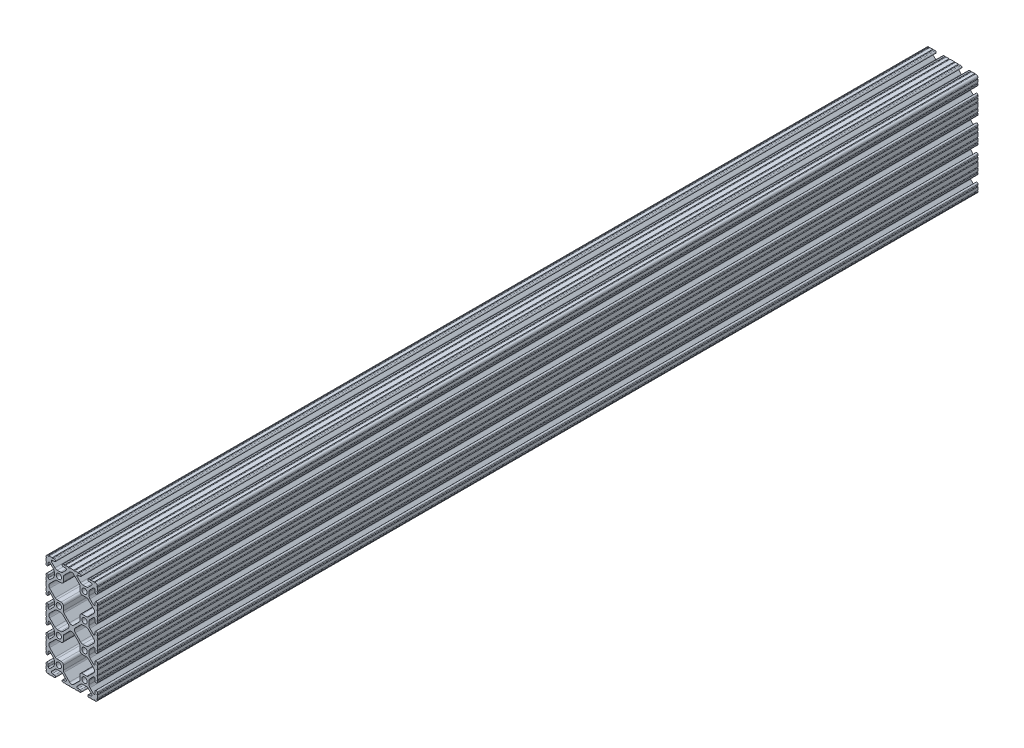
SolidWorks part; units mm, degrees
ref_plane "Front Plane" through (0, 0, 0) normal (0, 0, 1) x (1, 0, 0)
ref_plane "Top Plane" through (0, 0, 0) normal (0, 1, 0) x (1, 0, 0)
ref_plane "Right Plane" through (0, 0, 0) normal (1, 0, 0) x (0, 0, -1)
sketch "Sketch1" plane through (0, 0, 0) normal (0, 0, 1) x (1, 0, 0)
  line L0 (2.286, 55.2958) -> (-2.0184, 55.2958)
  line L1 (-3.5809, 55.943) -> (-9.0725, 61.4345)
  line L2 (-9.0725, 65.5655) -> (-3.5809, 71.057)
  line L3 (-2.0184, 71.7042) -> (2.286, 71.7042)
  line L4 (4.4958, 73.914) -> (4.4958, 78.2184)
  line L5 (5.143, 79.7809) -> (10.6345, 85.2725)
  line L6 (14.7655, 85.2725) -> (20.257, 79.7809)
  line L7 (20.9042, 78.2184) -> (20.9042, 73.914)
  line L8 (23.114, 71.7042) -> (27.4184, 71.7042)
  line L9 (28.9809, 71.057) -> (34.4725, 65.5655)
  line L10 (34.4725, 61.4345) -> (28.9809, 55.943)
  line L11 (27.4184, 55.2958) -> (23.114, 55.2958)
  line L12 (20.9042, 53.086) -> (20.9042, 48.7816)
  line L13 (20.257, 47.2191) -> (14.7655, 41.7275)
  line L14 (10.6345, 41.7275) -> (5.143, 47.2191)
  line L15 (4.4958, 48.7816) -> (4.4958, 53.086)
  line L16 (4.4958, 23.114) -> (4.4958, 27.4184)
  line L17 (5.143, 28.9809) -> (10.6345, 34.4725)
  line L18 (14.7655, 34.4725) -> (20.257, 28.9809)
  line L19 (20.9042, 27.4184) -> (20.9042, 23.114)
  line L20 (23.114, 20.9042) -> (27.4184, 20.9042)
  line L21 (28.9809, 20.257) -> (34.4725, 14.7655)
  line L22 (34.4725, 10.6345) -> (28.9809, 5.143)
  line L23 (27.4184, 4.4958) -> (23.114, 4.4958)
  line L24 (20.9042, 2.286) -> (20.9042, -2.0184)
  line L25 (20.257, -3.5809) -> (14.7655, -9.0725)
  line L26 (10.6345, -9.0725) -> (5.143, -3.5809)
  line L27 (4.4958, -2.0184) -> (4.4958, 2.286)
  line L28 (2.286, 4.4958) -> (-2.0184, 4.4958)
  line L29 (-3.5809, 5.143) -> (-9.0725, 10.6345)
  line L30 (-9.0725, 14.7655) -> (-3.5809, 20.257)
  line L31 (-2.0184, 20.9042) -> (2.286, 20.9042)
  line L32 (27.0186, 29.8958) -> (23.7824, 29.8958)
  line L33 (21.5373, 30.8258) -> (16.3286, 36.0346)
  line L34 (16.3286, 40.1654) -> (21.5373, 45.3742)
  line L35 (23.7824, 46.3042) -> (27.0186, 46.3042)
  line L36 (29.2636, 45.3743) -> (34.4725, 40.1655)
  line L37 (34.4725, 36.0345) -> (29.2636, 30.8257)
  line L38 (1.6176, 29.8958) -> (-1.6186, 29.8958)
  line L39 (-3.8636, 30.8257) -> (-9.0725, 36.0345)
  line L40 (-9.0725, 40.1655) -> (-3.8636, 45.3743)
  line L41 (-1.6186, 46.3042) -> (1.6176, 46.3042)
  line L42 (3.8627, 45.3742) -> (9.0714, 40.1654)
  line L43 (9.0714, 36.0346) -> (3.8627, 30.8258)
  line L44 (-12.7, 40.2336) -> (-12.7, 35.9664)
  line L45 (-12.7, 34.9504) -> (-12.7, 32.004)
  line L46 (-12.7, 30.988) -> (-12.7, 29.7434)
  line L47 (-10.4902, 29.7434) -> (-10.4902, 31.8743)
  line L48 (-8.7558, 32.5927) -> (-5.4258, 29.2627)
  line L49 (-4.4958, 27.0176) -> (-4.4958, 23.7824)
  line L50 (-5.4258, 21.5373) -> (-8.7558, 18.2073)
  line L51 (-10.4902, 18.9257) -> (-10.4902, 21.0566)
  line L52 (-12.7, 21.0566) -> (-12.7, 19.812)
  line L53 (-12.7, 18.796) -> (-12.7, 15.8496)
  line L54 (-12.7, 14.8336) -> (-12.7, 10.5664)
  line L55 (-12.7, 9.5504) -> (-12.7, 6.604)
  line L56 (-12.7, 5.588) -> (-12.7, 4.3434)
  line L57 (-10.4902, 4.3434) -> (-10.4902, 6.4743)
  line L58 (-8.7558, 7.1927) -> (-5.4258, 3.8627)
  line L59 (-4.4958, 1.6176) -> (-4.4958, -1.6176)
  line L60 (-5.4258, -3.8627) -> (-8.7558, -7.1927)
  line L61 (-10.4902, -6.4743) -> (-10.4902, -4.3434)
  line L62 (-12.7, -4.3434) -> (-12.7, -5.588)
  line L63 (-12.7, -6.604) -> (-12.7, -9.5504)
  line L64 (-9.5504, -12.7) -> (-6.604, -12.7)
  line L65 (-5.588, -12.7) -> (-4.3434, -12.7)
  line L66 (-4.3434, -10.4902) -> (-6.4743, -10.4902)
  line L67 (-7.1927, -8.7558) -> (-3.8627, -5.4258)
  line L68 (-1.6176, -4.4958) -> (1.6176, -4.4958)
  line L69 (3.8627, -5.4258) -> (7.1927, -8.7558)
  line L70 (6.4743, -10.4902) -> (4.3434, -10.4902)
  line L71 (4.3434, -12.7) -> (5.588, -12.7)
  line L72 (6.604, -12.7) -> (9.5504, -12.7)
  line L73 (10.5664, -12.7) -> (14.8336, -12.7)
  line L74 (15.8496, -12.7) -> (18.796, -12.7)
  line L75 (19.812, -12.7) -> (21.0566, -12.7)
  line L76 (21.0566, -10.4902) -> (18.9257, -10.4902)
  line L77 (18.2073, -8.7558) -> (21.5373, -5.4258)
  line L78 (23.7824, -4.4958) -> (27.0176, -4.4958)
  line L79 (29.2627, -5.4258) -> (32.5927, -8.7558)
  line L80 (31.8743, -10.4902) -> (29.7434, -10.4902)
  line L81 (29.7434, -12.7) -> (30.988, -12.7)
  line L82 (32.004, -12.7) -> (34.9504, -12.7)
  line L83 (38.1, -9.5504) -> (38.1, -6.604)
  line L84 (38.1, -5.588) -> (38.1, -4.3434)
  line L85 (35.8902, -4.3434) -> (35.8902, -6.4743)
  line L86 (34.1558, -7.1927) -> (30.8258, -3.8627)
  line L87 (29.8958, -1.6176) -> (29.8958, 1.6176)
  line L88 (30.8258, 3.8627) -> (34.1558, 7.1927)
  line L89 (35.8902, 6.4743) -> (35.8902, 4.3434)
  line L90 (38.1, 4.3434) -> (38.1, 5.588)
  line L91 (38.1, 6.604) -> (38.1, 9.5504)
  line L92 (38.1, 10.5664) -> (38.1, 14.8336)
  line L93 (38.1, 15.8496) -> (38.1, 18.796)
  line L94 (38.1, 19.812) -> (38.1, 21.0566)
  line L95 (35.8902, 21.0566) -> (35.8902, 18.9257)
  line L96 (34.1558, 18.2073) -> (30.8258, 21.5373)
  line L97 (29.8958, 23.7824) -> (29.8958, 27.0176)
  line L98 (30.8258, 29.2627) -> (34.1558, 32.5927)
  line L99 (35.8902, 31.8743) -> (35.8902, 29.7434)
  line L100 (38.1, 29.7434) -> (38.1, 30.988)
  line L101 (38.1, 32.004) -> (38.1, 34.9504)
  line L102 (38.1, 35.9664) -> (38.1, 40.2336)
  line L103 (38.1, 41.2496) -> (38.1, 44.196)
  line L104 (38.1, 45.212) -> (38.1, 46.4566)
  line L105 (35.8902, 46.4566) -> (35.8902, 44.3257)
  line L106 (34.1558, 43.6073) -> (30.8258, 46.9373)
  line L107 (29.8958, 49.1824) -> (29.8958, 52.4176)
  line L108 (30.8258, 54.6627) -> (34.1558, 57.9927)
  line L109 (35.8902, 57.2743) -> (35.8902, 55.1434)
  line L110 (38.1, 55.1434) -> (38.1, 56.388)
  line L111 (38.1, 57.404) -> (38.1, 60.3504)
  line L112 (38.1, 61.3664) -> (38.1, 65.6336)
  line L113 (38.1, 66.6496) -> (38.1, 69.596)
  line L114 (38.1, 70.612) -> (38.1, 71.8566)
  line L115 (35.8902, 71.8566) -> (35.8902, 69.7257)
  line L116 (34.1558, 69.0073) -> (30.8258, 72.3373)
  line L117 (29.8958, 74.5824) -> (29.8958, 77.8176)
  line L118 (30.8258, 80.0627) -> (34.1558, 83.3927)
  line L119 (35.8902, 82.6743) -> (35.8902, 80.5434)
  line L120 (38.1, 80.5434) -> (38.1, 81.788)
  line L121 (38.1, 82.804) -> (38.1, 85.7504)
  line L122 (34.9504, 88.9) -> (32.004, 88.9)
  line L123 (30.988, 88.9) -> (29.7434, 88.9)
  line L124 (29.7434, 86.6902) -> (31.8743, 86.6902)
  line L125 (32.5927, 84.9558) -> (29.2627, 81.6258)
  line L126 (27.0176, 80.6958) -> (23.7824, 80.6958)
  line L127 (21.5373, 81.6258) -> (18.2073, 84.9558)
  line L128 (18.9257, 86.6902) -> (21.0566, 86.6902)
  line L129 (21.0566, 88.9) -> (19.812, 88.9)
  line L130 (18.796, 88.9) -> (15.8496, 88.9)
  line L131 (14.8336, 88.9) -> (10.5664, 88.9)
  line L132 (9.5504, 88.9) -> (6.604, 88.9)
  line L133 (5.588, 88.9) -> (4.3434, 88.9)
  line L134 (4.3434, 86.6902) -> (6.4743, 86.6902)
  line L135 (7.1927, 84.9558) -> (3.8627, 81.6258)
  line L136 (1.6176, 80.6958) -> (-1.6176, 80.6958)
  line L137 (-3.8627, 81.6258) -> (-7.1927, 84.9558)
  line L138 (-6.4743, 86.6902) -> (-4.3434, 86.6902)
  line L139 (-4.3434, 88.9) -> (-5.588, 88.9)
  line L140 (-6.604, 88.9) -> (-9.5504, 88.9)
  line L141 (-12.7, 85.7504) -> (-12.7, 82.804)
  line L142 (-12.7, 81.788) -> (-12.7, 80.5434)
  line L143 (-10.4902, 80.5434) -> (-10.4902, 82.6743)
  line L144 (-8.7558, 83.3927) -> (-5.4258, 80.0627)
  line L145 (-4.4958, 77.8176) -> (-4.4958, 74.5824)
  line L146 (-5.4258, 72.3373) -> (-8.7558, 69.0073)
  line L147 (-10.4902, 69.7257) -> (-10.4902, 71.8566)
  line L148 (-12.7, 71.8566) -> (-12.7, 70.612)
  line L149 (-12.7, 69.596) -> (-12.7, 66.6496)
  line L150 (-12.7, 65.6336) -> (-12.7, 61.3664)
  line L151 (-12.7, 60.3504) -> (-12.7, 57.404)
  line L152 (-12.7, 56.388) -> (-12.7, 55.1434)
  line L153 (-10.4902, 55.1434) -> (-10.4902, 57.2743)
  line L154 (-8.7558, 57.9927) -> (-5.4258, 54.6627)
  line L155 (-4.4958, 52.4176) -> (-4.4958, 49.1824)
  line L156 (-5.4258, 46.9373) -> (-8.7558, 43.6073)
  line L157 (-10.4902, 44.3257) -> (-10.4902, 46.4566)
  line L158 (-12.7, 46.4566) -> (-12.7, 45.212)
  line L159 (-12.7, 44.196) -> (-12.7, 41.2496)
  arc A0 (4.4958, 53.086) -> (2.286, 55.2958) centre (2.286, 53.086) ccw
  arc A1 (-3.5809, 55.943) -> (-2.0184, 55.2958) centre (-2.0184, 57.5056) ccw
  arc A2 (-9.0725, 65.5655) -> (-9.0725, 61.4345) centre (-7.0071, 63.5) ccw
  arc A3 (-2.0184, 71.7042) -> (-3.5809, 71.057) centre (-2.0184, 69.4944) ccw
  arc A4 (2.286, 71.7042) -> (4.4958, 73.914) centre (2.286, 73.914) ccw
  arc A5 (5.143, 79.7809) -> (4.4958, 78.2184) centre (6.7056, 78.2184) ccw
  arc A6 (14.7655, 85.2725) -> (10.6345, 85.2725) centre (12.7, 83.2071) ccw
  arc A7 (20.9042, 78.2184) -> (20.257, 79.7809) centre (18.6944, 78.2184) ccw
  arc A8 (20.9042, 73.914) -> (23.114, 71.7042) centre (23.114, 73.914) ccw
  arc A9 (28.9809, 71.057) -> (27.4184, 71.7042) centre (27.4184, 69.4944) ccw
  arc A10 (34.4725, 61.4345) -> (34.4725, 65.5655) centre (32.4071, 63.5) ccw
  arc A11 (27.4184, 55.2958) -> (28.9809, 55.943) centre (27.4184, 57.5056) ccw
  arc A12 (23.114, 55.2958) -> (20.9042, 53.086) centre (23.114, 53.086) ccw
  arc A13 (20.257, 47.2191) -> (20.9042, 48.7816) centre (18.6944, 48.7816) ccw
  arc A14 (10.6345, 41.7275) -> (14.7655, 41.7275) centre (12.7, 43.7929) ccw
  arc A15 (4.4958, 48.7816) -> (5.143, 47.2191) centre (6.7056, 48.7816) ccw
  arc A16 (2.286, 20.9042) -> (4.4958, 23.114) centre (2.286, 23.114) ccw
  arc A17 (5.143, 28.9809) -> (4.4958, 27.4184) centre (6.7056, 27.4184) ccw
  arc A18 (14.7655, 34.4725) -> (10.6345, 34.4725) centre (12.7, 32.4071) ccw
  arc A19 (20.9042, 27.4184) -> (20.257, 28.9809) centre (18.6944, 27.4184) ccw
  arc A20 (20.9042, 23.114) -> (23.114, 20.9042) centre (23.114, 23.114) ccw
  arc A21 (28.9809, 20.257) -> (27.4184, 20.9042) centre (27.4184, 18.6944) ccw
  arc A22 (34.4725, 10.6345) -> (34.4725, 14.7655) centre (32.4071, 12.7) ccw
  arc A23 (27.4184, 4.4958) -> (28.9809, 5.143) centre (27.4184, 6.7056) ccw
  arc A24 (23.114, 4.4958) -> (20.9042, 2.286) centre (23.114, 2.286) ccw
  arc A25 (20.257, -3.5809) -> (20.9042, -2.0184) centre (18.6944, -2.0184) ccw
  arc A26 (10.6345, -9.0725) -> (14.7655, -9.0725) centre (12.7, -7.0071) ccw
  arc A27 (4.4958, -2.0184) -> (5.143, -3.5809) centre (6.7056, -2.0184) ccw
  arc A28 (4.4958, 2.286) -> (2.286, 4.4958) centre (2.286, 2.286) ccw
  arc A29 (-3.5809, 5.143) -> (-2.0184, 4.4958) centre (-2.0184, 6.7056) ccw
  arc A30 (-9.0725, 14.7655) -> (-9.0725, 10.6345) centre (-7.0071, 12.7) ccw
  arc A31 (-2.0184, 20.9042) -> (-3.5809, 20.257) centre (-2.0184, 18.6944) ccw
  arc A32 (27.0186, 29.8958) -> (29.2636, 30.8257) centre (27.0186, 33.0708) ccw
  arc A33 (21.5373, 30.8258) -> (23.7824, 29.8958) centre (23.7824, 33.0708) ccw
  arc A34 (16.3286, 40.1654) -> (16.3286, 36.0346) centre (18.3941, 38.1) ccw
  arc A35 (23.7824, 46.3042) -> (21.5373, 45.3742) centre (23.7824, 43.1292) ccw
  arc A36 (29.2636, 45.3743) -> (27.0186, 46.3042) centre (27.0186, 43.1292) ccw
  arc A37 (34.4725, 36.0345) -> (34.4725, 40.1655) centre (32.4071, 38.1) ccw
  arc A38 (1.6176, 29.8958) -> (3.8627, 30.8258) centre (1.6176, 33.0708) ccw
  arc A39 (-3.8636, 30.8257) -> (-1.6186, 29.8958) centre (-1.6186, 33.0708) ccw
  arc A40 (-9.0725, 40.1655) -> (-9.0725, 36.0345) centre (-7.0071, 38.1) ccw
  arc A41 (-1.6186, 46.3042) -> (-3.8636, 45.3743) centre (-1.6186, 43.1292) ccw
  arc A42 (3.8627, 45.3742) -> (1.6176, 46.3042) centre (1.6176, 43.1292) ccw
  arc A43 (9.0714, 36.0346) -> (9.0714, 40.1654) centre (7.0059, 38.1) ccw
  circle A44 centre (25.4, 76.2) radius 2.6035
  circle A45 centre (0, 76.2) radius 2.6035
  circle A46 centre (25.4, 50.8) radius 2.6035
  circle A47 centre (0, 50.8) radius 2.6035
  circle A48 centre (25.4, 0) radius 2.6035
  circle A49 centre (0, 0) radius 2.6035
  circle A50 centre (25.4, 25.4) radius 2.6035
  circle A51 centre (0, 25.4) radius 2.6035
  arc A52 (-12.7, 34.9504) -> (-12.7, 35.9664) centre (-12.7, 35.4584) ccw
  arc A53 (-12.7, 30.988) -> (-12.7, 32.004) centre (-12.7, 31.496) ccw
  arc A54 (-12.7, 29.7434) -> (-10.4902, 29.7434) centre (-11.5951, 29.7434) ccw
  arc A55 (-8.7558, 32.5927) -> (-10.4902, 31.8743) centre (-9.4742, 31.8743) ccw
  arc A56 (-4.4958, 27.0176) -> (-5.4258, 29.2627) centre (-7.6708, 27.0176) ccw
  arc A57 (-5.4258, 21.5373) -> (-4.4958, 23.7824) centre (-7.6708, 23.7824) ccw
  arc A58 (-10.4902, 18.9257) -> (-8.7558, 18.2073) centre (-9.4742, 18.9257) ccw
  arc A59 (-10.4902, 21.0566) -> (-12.7, 21.0566) centre (-11.5951, 21.0566) ccw
  arc A60 (-12.7, 18.796) -> (-12.7, 19.812) centre (-12.7, 19.304) ccw
  arc A61 (-12.7, 14.8336) -> (-12.7, 15.8496) centre (-12.7, 15.3416) ccw
  arc A62 (-12.7, 9.5504) -> (-12.7, 10.5664) centre (-12.7, 10.0584) ccw
  arc A63 (-12.7, 5.588) -> (-12.7, 6.604) centre (-12.7, 6.096) ccw
  arc A64 (-12.7, 4.3434) -> (-10.4902, 4.3434) centre (-11.5951, 4.3434) ccw
  arc A65 (-8.7558, 7.1927) -> (-10.4902, 6.4743) centre (-9.4742, 6.4743) ccw
  arc A66 (-4.4958, 1.6176) -> (-5.4258, 3.8627) centre (-7.6708, 1.6176) ccw
  arc A67 (-5.4258, -3.8627) -> (-4.4958, -1.6176) centre (-7.6708, -1.6176) ccw
  arc A68 (-10.4902, -6.4743) -> (-8.7558, -7.1927) centre (-9.4742, -6.4743) ccw
  arc A69 (-10.4902, -4.3434) -> (-12.7, -4.3434) centre (-11.5951, -4.3434) ccw
  arc A70 (-12.7, -6.604) -> (-12.7, -5.588) centre (-12.7, -6.096) ccw
  arc A71 (-12.6998, -10.5664) -> (-12.7, -9.5504) centre (-12.7, -10.0584) ccw
  arc A72 (-12.6998, -10.5664) -> (-10.5664, -12.6998) centre (-10.5918, -10.5918) ccw
  arc A73 (-9.5504, -12.7) -> (-10.5664, -12.6998) centre (-10.0584, -12.7) ccw
  arc A74 (-5.588, -12.7) -> (-6.604, -12.7) centre (-6.096, -12.7) ccw
  arc A75 (-4.3434, -12.7) -> (-4.3434, -10.4902) centre (-4.3434, -11.5951) ccw
  arc A76 (-7.1927, -8.7558) -> (-6.4743, -10.4902) centre (-6.4743, -9.4742) ccw
  arc A77 (-1.6176, -4.4958) -> (-3.8627, -5.4258) centre (-1.6176, -7.6708) ccw
  arc A78 (3.8627, -5.4258) -> (1.6176, -4.4958) centre (1.6176, -7.6708) ccw
  arc A79 (6.4743, -10.4902) -> (7.1927, -8.7558) centre (6.4743, -9.4742) ccw
  arc A80 (4.3434, -10.4902) -> (4.3434, -12.7) centre (4.3434, -11.5951) ccw
  arc A81 (6.604, -12.7) -> (5.588, -12.7) centre (6.096, -12.7) ccw
  arc A82 (10.5664, -12.7) -> (9.5504, -12.7) centre (10.0584, -12.7) ccw
  arc A83 (15.8496, -12.7) -> (14.8336, -12.7) centre (15.3416, -12.7) ccw
  arc A84 (19.812, -12.7) -> (18.796, -12.7) centre (19.304, -12.7) ccw
  arc A85 (21.0566, -12.7) -> (21.0566, -10.4902) centre (21.0566, -11.5951) ccw
  arc A86 (18.2073, -8.7558) -> (18.9257, -10.4902) centre (18.9257, -9.4742) ccw
  arc A87 (23.7824, -4.4958) -> (21.5373, -5.4258) centre (23.7824, -7.6708) ccw
  arc A88 (29.2627, -5.4258) -> (27.0176, -4.4958) centre (27.0176, -7.6708) ccw
  arc A89 (31.8743, -10.4902) -> (32.5927, -8.7558) centre (31.8743, -9.4742) ccw
  arc A90 (29.7434, -10.4902) -> (29.7434, -12.7) centre (29.7434, -11.5951) ccw
  arc A91 (32.004, -12.7) -> (30.988, -12.7) centre (31.496, -12.7) ccw
  arc A92 (35.9664, -12.6998) -> (34.9504, -12.7) centre (35.4584, -12.7) ccw
  arc A93 (35.9664, -12.6998) -> (38.0998, -10.5664) centre (35.9918, -10.5918) ccw
  arc A94 (38.1, -9.5504) -> (38.0998, -10.5664) centre (38.1, -10.0584) ccw
  arc A95 (38.1, -5.588) -> (38.1, -6.604) centre (38.1, -6.096) ccw
  arc A96 (38.1, -4.3434) -> (35.8902, -4.3434) centre (36.9951, -4.3434) ccw
  arc A97 (34.1558, -7.1927) -> (35.8902, -6.4743) centre (34.8742, -6.4743) ccw
  arc A98 (29.8958, -1.6176) -> (30.8258, -3.8627) centre (33.0708, -1.6176) ccw
  arc A99 (30.8258, 3.8627) -> (29.8958, 1.6176) centre (33.0708, 1.6176) ccw
  arc A100 (35.8902, 6.4743) -> (34.1558, 7.1927) centre (34.8742, 6.4743) ccw
  arc A101 (35.8902, 4.3434) -> (38.1, 4.3434) centre (36.9951, 4.3434) ccw
  arc A102 (38.1, 6.604) -> (38.1, 5.588) centre (38.1, 6.096) ccw
  arc A103 (38.1, 10.5664) -> (38.1, 9.5504) centre (38.1, 10.0584) ccw
  arc A104 (38.1, 15.8496) -> (38.1, 14.8336) centre (38.1, 15.3416) ccw
  arc A105 (38.1, 19.812) -> (38.1, 18.796) centre (38.1, 19.304) ccw
  arc A106 (38.1, 21.0566) -> (35.8902, 21.0566) centre (36.9951, 21.0566) ccw
  arc A107 (34.1558, 18.2073) -> (35.8902, 18.9257) centre (34.8742, 18.9257) ccw
  arc A108 (29.8958, 23.7824) -> (30.8258, 21.5373) centre (33.0708, 23.7824) ccw
  arc A109 (30.8258, 29.2627) -> (29.8958, 27.0176) centre (33.0708, 27.0176) ccw
  arc A110 (35.8902, 31.8743) -> (34.1558, 32.5927) centre (34.8742, 31.8743) ccw
  arc A111 (35.8902, 29.7434) -> (38.1, 29.7434) centre (36.9951, 29.7434) ccw
  arc A112 (38.1, 32.004) -> (38.1, 30.988) centre (38.1, 31.496) ccw
  arc A113 (38.1, 35.9664) -> (38.1, 34.9504) centre (38.1, 35.4584) ccw
  arc A114 (38.1, 41.2496) -> (38.1, 40.2336) centre (38.1, 40.7416) ccw
  arc A115 (38.1, 45.212) -> (38.1, 44.196) centre (38.1, 44.704) ccw
  arc A116 (38.1, 46.4566) -> (35.8902, 46.4566) centre (36.9951, 46.4566) ccw
  arc A117 (34.1558, 43.6073) -> (35.8902, 44.3257) centre (34.8742, 44.3257) ccw
  arc A118 (29.8958, 49.1824) -> (30.8258, 46.9373) centre (33.0708, 49.1824) ccw
  arc A119 (30.8258, 54.6627) -> (29.8958, 52.4176) centre (33.0708, 52.4176) ccw
  arc A120 (35.8902, 57.2743) -> (34.1558, 57.9927) centre (34.8742, 57.2743) ccw
  arc A121 (35.8902, 55.1434) -> (38.1, 55.1434) centre (36.9951, 55.1434) ccw
  arc A122 (38.1, 57.404) -> (38.1, 56.388) centre (38.1, 56.896) ccw
  arc A123 (38.1, 61.3664) -> (38.1, 60.3504) centre (38.1, 60.8584) ccw
  arc A124 (38.1, 66.6496) -> (38.1, 65.6336) centre (38.1, 66.1416) ccw
  arc A125 (38.1, 70.612) -> (38.1, 69.596) centre (38.1, 70.104) ccw
  arc A126 (38.1, 71.8566) -> (35.8902, 71.8566) centre (36.9951, 71.8566) ccw
  arc A127 (34.1558, 69.0073) -> (35.8902, 69.7257) centre (34.8742, 69.7257) ccw
  arc A128 (29.8958, 74.5824) -> (30.8258, 72.3373) centre (33.0708, 74.5824) ccw
  arc A129 (30.8258, 80.0627) -> (29.8958, 77.8176) centre (33.0708, 77.8176) ccw
  arc A130 (35.8902, 82.6743) -> (34.1558, 83.3927) centre (34.8742, 82.6743) ccw
  arc A131 (35.8902, 80.5434) -> (38.1, 80.5434) centre (36.9951, 80.5434) ccw
  arc A132 (38.1, 82.804) -> (38.1, 81.788) centre (38.1, 82.296) ccw
  arc A133 (38.0998, 86.7664) -> (38.1, 85.7504) centre (38.1, 86.2584) ccw
  arc A134 (38.0998, 86.7664) -> (35.9664, 88.8998) centre (35.9918, 86.7918) ccw
  arc A135 (34.9504, 88.9) -> (35.9664, 88.8998) centre (35.4584, 88.9) ccw
  arc A136 (30.988, 88.9) -> (32.004, 88.9) centre (31.496, 88.9) ccw
  arc A137 (29.7434, 88.9) -> (29.7434, 86.6902) centre (29.7434, 87.7951) ccw
  arc A138 (32.5927, 84.9558) -> (31.8743, 86.6902) centre (31.8743, 85.6742) ccw
  arc A139 (27.0176, 80.6958) -> (29.2627, 81.6258) centre (27.0176, 83.8708) ccw
  arc A140 (21.5373, 81.6258) -> (23.7824, 80.6958) centre (23.7824, 83.8708) ccw
  arc A141 (18.9257, 86.6902) -> (18.2073, 84.9558) centre (18.9257, 85.6742) ccw
  arc A142 (21.0566, 86.6902) -> (21.0566, 88.9) centre (21.0566, 87.7951) ccw
  arc A143 (18.796, 88.9) -> (19.812, 88.9) centre (19.304, 88.9) ccw
  arc A144 (14.8336, 88.9) -> (15.8496, 88.9) centre (15.3416, 88.9) ccw
  arc A145 (9.5504, 88.9) -> (10.5664, 88.9) centre (10.0584, 88.9) ccw
  arc A146 (5.588, 88.9) -> (6.604, 88.9) centre (6.096, 88.9) ccw
  arc A147 (4.3434, 88.9) -> (4.3434, 86.6902) centre (4.3434, 87.7951) ccw
  arc A148 (7.1927, 84.9558) -> (6.4743, 86.6902) centre (6.4743, 85.6742) ccw
  arc A149 (1.6176, 80.6958) -> (3.8627, 81.6258) centre (1.6176, 83.8708) ccw
  arc A150 (-3.8627, 81.6258) -> (-1.6176, 80.6958) centre (-1.6176, 83.8708) ccw
  arc A151 (-6.4743, 86.6902) -> (-7.1927, 84.9558) centre (-6.4743, 85.6742) ccw
  arc A152 (-4.3434, 86.6902) -> (-4.3434, 88.9) centre (-4.3434, 87.7951) ccw
  arc A153 (-6.604, 88.9) -> (-5.588, 88.9) centre (-6.096, 88.9) ccw
  arc A154 (-10.5664, 88.8998) -> (-9.5504, 88.9) centre (-10.0584, 88.9) ccw
  arc A155 (-10.5664, 88.8998) -> (-12.6998, 86.7664) centre (-10.5918, 86.7918) ccw
  arc A156 (-12.7, 85.7504) -> (-12.6998, 86.7664) centre (-12.7, 86.2584) ccw
  arc A157 (-12.7, 81.788) -> (-12.7, 82.804) centre (-12.7, 82.296) ccw
  arc A158 (-12.7, 80.5434) -> (-10.4902, 80.5434) centre (-11.5951, 80.5434) ccw
  arc A159 (-8.7558, 83.3927) -> (-10.4902, 82.6743) centre (-9.4742, 82.6743) ccw
  arc A160 (-4.4958, 77.8176) -> (-5.4258, 80.0627) centre (-7.6708, 77.8176) ccw
  arc A161 (-5.4258, 72.3373) -> (-4.4958, 74.5824) centre (-7.6708, 74.5824) ccw
  arc A162 (-10.4902, 69.7257) -> (-8.7558, 69.0073) centre (-9.4742, 69.7257) ccw
  arc A163 (-10.4902, 71.8566) -> (-12.7, 71.8566) centre (-11.5951, 71.8566) ccw
  arc A164 (-12.7, 69.596) -> (-12.7, 70.612) centre (-12.7, 70.104) ccw
  arc A165 (-12.7, 65.6336) -> (-12.7, 66.6496) centre (-12.7, 66.1416) ccw
  arc A166 (-12.7, 60.3504) -> (-12.7, 61.3664) centre (-12.7, 60.8584) ccw
  arc A167 (-12.7, 56.388) -> (-12.7, 57.404) centre (-12.7, 56.896) ccw
  arc A168 (-12.7, 55.1434) -> (-10.4902, 55.1434) centre (-11.5951, 55.1434) ccw
  arc A169 (-8.7558, 57.9927) -> (-10.4902, 57.2743) centre (-9.4742, 57.2743) ccw
  arc A170 (-4.4958, 52.4176) -> (-5.4258, 54.6627) centre (-7.6708, 52.4176) ccw
  arc A171 (-5.4258, 46.9373) -> (-4.4958, 49.1824) centre (-7.6708, 49.1824) ccw
  arc A172 (-10.4902, 44.3257) -> (-8.7558, 43.6073) centre (-9.4742, 44.3257) ccw
  arc A173 (-10.4902, 46.4566) -> (-12.7, 46.4566) centre (-11.5951, 46.4566) ccw
  arc A174 (-12.7, 44.196) -> (-12.7, 45.212) centre (-12.7, 44.704) ccw
  arc A175 (-12.7, 40.2336) -> (-12.7, 41.2496) centre (-12.7, 40.7416) ccw
extrude "Extrude1" add sketch "Sketch1" against normal blind 871.728
